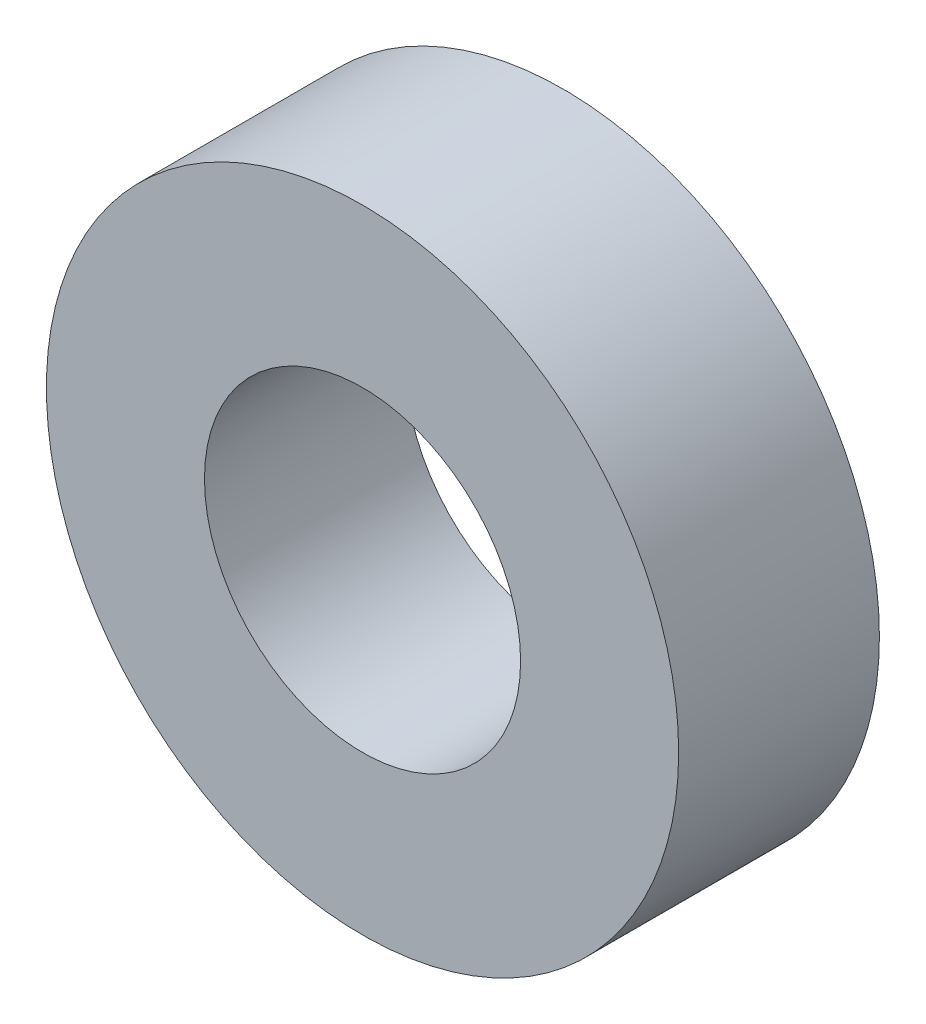
SolidWorks part; units mm, degrees
ref_plane "Front Plane" through (0, 0, 0) normal (0, 0, 1) x (1, 0, 0)
ref_plane "Top Plane" through (0, 0, 0) normal (0, 1, 0) x (1, 0, 0)
ref_plane "Right Plane" through (0, 0, 0) normal (1, 0, 0) x (0, 0, -1)
sketch "Sketch1" plane through (0, 0, 0) normal (0, 0, 1) x (1, 0, 0)
  circle A0 centre (0, 0) radius 4
  circle A1 centre (0, 0) radius 2
  dimension "D1" = 8
  dimension "D2" = 4
extrude "Boss-Extrude1" add sketch "Sketch1" along normal blind 2.54
